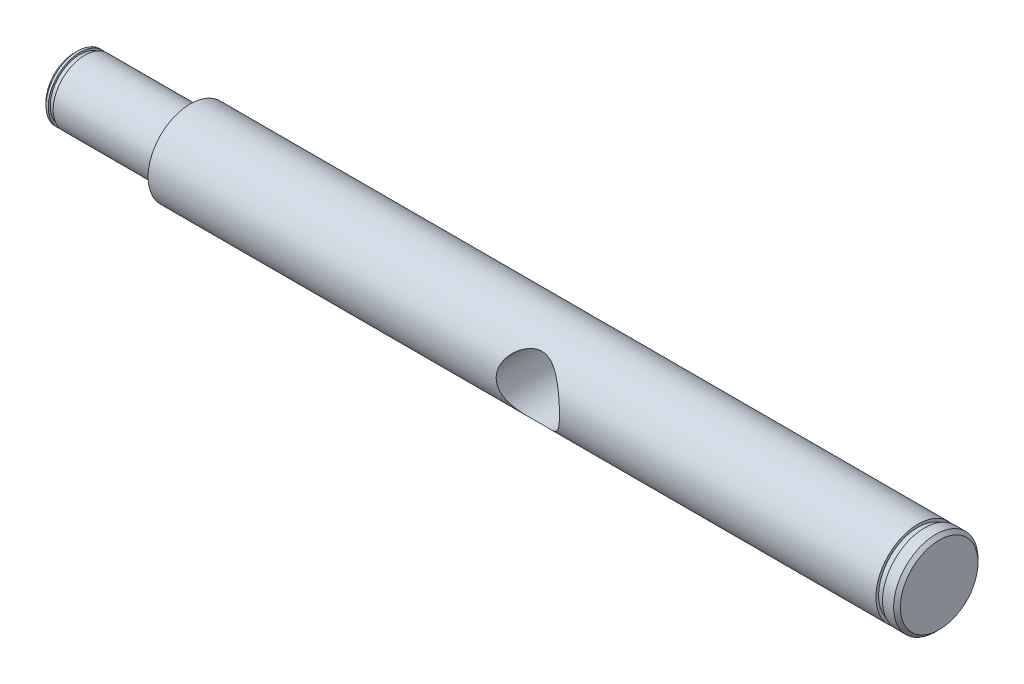
SolidWorks part; units mm, degrees
material "AISI 1020 Steel, Cold Rolled"
ref_plane "Front Plane" through (0, 0, 0) normal (0, 0, 1) x (1, 0, 0)
ref_plane "Top Plane" through (0, 0, 0) normal (0, 1, 0) x (1, 0, 0)
ref_plane "Right Plane" through (0, 0, 0) normal (1, 0, 0) x (0, 0, -1)
sketch "Sketch1" plane through (0, 0, 0) normal (0, 0, 1) x (1, 0, 0)
  line L0 (0, 0) -> (-86.7362, 0) construction
  line L1 (-57.15, 6.35) -> (52.3875, 6.35)
  line L2 (-57.15, 6.35) -> (-57.15, 4.7625)
  line L3 (-57.15, 4.7625) -> (-73.025, 4.7625)
  line L4 (-73.025, 4.7625) -> (-73.025, 4.4704)
  line L5 (-73.025, 4.4704) -> (-73.7616, 4.4704)
  line L6 (-73.7616, 4.4704) -> (-73.7616, 4.7625)
  line L7 (-73.7616, 4.7625) -> (-74.6125, 4.7625)
  line L8 (-74.6125, 4.7625) -> (-74.6125, 0)
  line L9 (-74.6125, 0) -> (55.5625, 0)
  line L10 (55.5625, 0) -> (55.5625, 6.35)
  line L11 (55.5625, 6.35) -> (53.3781, 6.35)
  line L12 (53.3781, 6.35) -> (53.3781, 5.9436)
  line L13 (53.3781, 5.9436) -> (52.3875, 5.9436)
  line L14 (52.3875, 5.9436) -> (52.3875, 6.35)
  dimension "D1" = 12.7
  dimension "D2" = 9.525
  dimension "D3" = 57.15
  dimension "D4" = 73.025
  dimension "D5" = 74.6125
  dimension "D6" = 0.7366
  dimension "D7" = 8.9408
  dimension "D8" = 0.9906
  dimension "D9" = 11.8872
  dimension "D10" = 55.5625
  dimension "D11" = 52.3875
revolve "Revolve1" add sketch "Sketch1" angle 360 about L0
sketch "Sketch2" plane through (0, 0, 0) normal (0, 0, 1) x (1, 0, 0)
  circle A0 centre (0, 0) radius 4.7625
  dimension "D1" = 9.525
extrude "Cut-Extrude1" cut sketch "Sketch2" against normal through all and the other way through all
chamfer "Chamfer1" distance 0.508 angle 45 2 edges at (-74.6125, 0, -4.7625) (55.5625, 0, -6.35)
